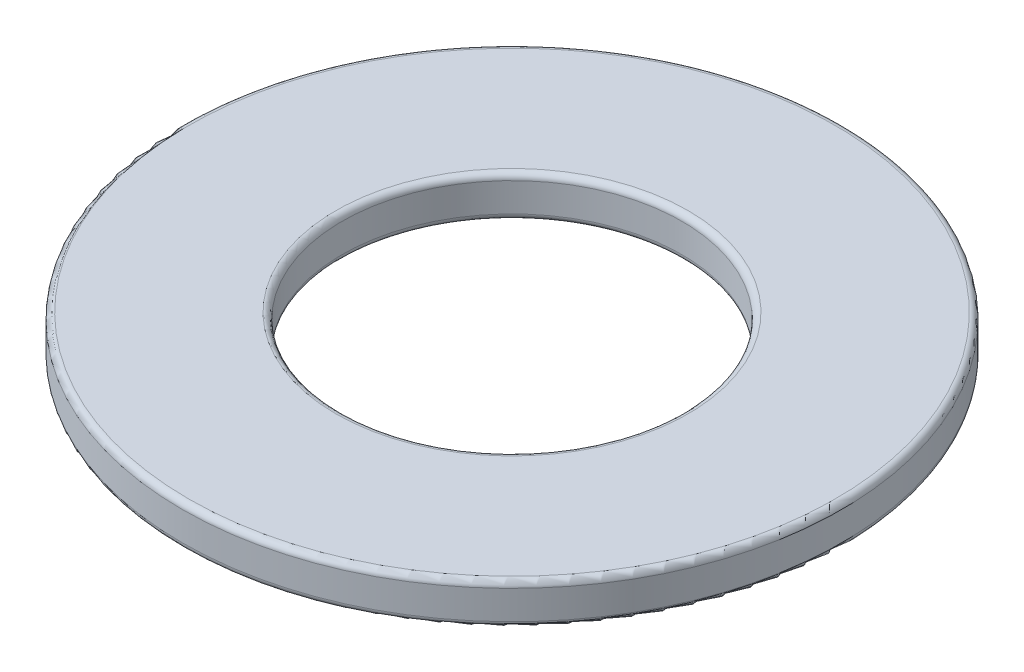
SolidWorks part; units mm, degrees
ref_plane "Front Plane" through (0, 0, 0) normal (0, 0, 1) x (1, 0, 0)
ref_plane "Top Plane" through (0, 0, 0) normal (0, 1, 0) x (1, 0, 0)
ref_plane "Right Plane" through (0, 0, 0) normal (1, 0, 0) x (0, 0, -1)
sketch "Sketch1" plane through (0, 0, 0) normal (0, 1, 0) x (1, 0, 0)
  circle A0 centre (0, 0) radius 4.125
  circle A1 centre (0, 0) radius 8
  dimension "D1" = 8.25
  dimension "D2" = 16
extrude "Boss-Extrude1" add sketch "Sketch1" along normal mid plane 1
fillet "Fillet1" radius 0.15 4 edges at (0, -0.5, 4.125) (0, 0.5, 4.125) (0, -0.5, 8) (0, 0.5, 8)
